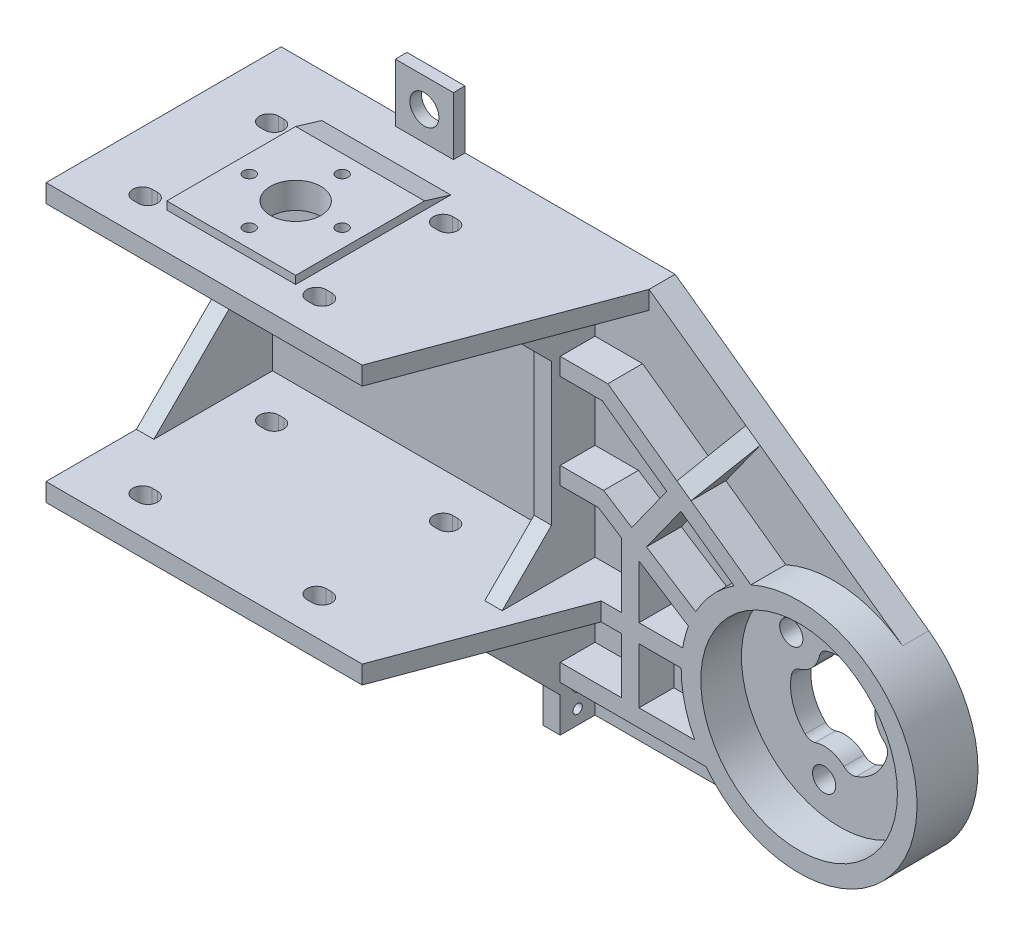
SolidWorks part; units mm, degrees
ref_plane "Alzado" through (0, 0, 0) normal (0, 0, 1) x (1, 0, 0)
ref_plane "Planta" through (0, 0, 0) normal (0, 1, 0) x (1, 0, 0)
ref_plane "Vista lateral" through (0, 0, 0) normal (1, 0, 0) x (0, 0, -1)
sketch "Croquis1" plane through (0, 0, 0) normal (0, 0, 1) x (1, 0, 0)
  line L1 (-98.9551, 43.6677) -> (22.1086, 43.6677)
  line L2 (-98.9551, 43.6677) -> (-98.9551, -24.473)
  line L3 (-98.9551, -24.473) -> (22.1086, -24.473)
  line L4 (22.1086, 43.6677) -> (22.1086, -24.473)
extrude "Saliente-Extruir1" add sketch "Croquis1" along normal blind 3 and the other way blind 1.5
sketch "Croquis2" plane through (0, 0, 3) normal (0, 0, 1) x (1, 0, 0)
  line L0 (-98.9551, 43.6677) -> (-98.9551, -24.473) construction
  line L1 (-98.9551, 43.6677) -> (-31.1073, 43.6677)
  line L2 (-98.9551, 43.6677) -> (-98.9551, 40.5377)
  line L3 (-98.9551, 40.5377) -> (-31.1073, 40.5377)
  line L4 (-31.1073, 43.6677) -> (-31.1073, 40.5377)
  line L5 (-98.9551, -4.0423) -> (-31.1073, -4.0423)
  line L6 (-98.9551, -4.0423) -> (-98.9551, -0.9123)
  line L7 (-98.9551, -0.9123) -> (-31.1073, -0.9123)
  line L8 (-31.1073, -4.0423) -> (-31.1073, -0.9123)
  dimension "D1" = 3.13
  dimension "D2" = 3.13
  dimension "D3" = 41.45
extrude "Saliente-Extruir2" add sketch "Croquis2" along normal blind 36
sketch "Croquis3" plane through (0, 43.6677, 0) normal (0, 1, 0) x (1, 0, 0)
  line L0 (-44.4942, -39) -> (-31.1073, -3)
  line L1 (-31.1073, -39) -> (-98.9551, -39) construction
  line L2 (-31.1073, -3) -> (-31.1073, -39)
  line L3 (-31.1073, -39) -> (-44.4942, -39)
extrude "Cortar-Extruir1" cut sketch "Croquis3" against normal up to surface (47.71 mm away) up to face at (-65.0312, -4.0423, 21)
sketch "Croquis4" plane through (-98.9551, 0, 0) normal (-1, 0, 0) x (0, 0, 1)
  line L0 (3, 40.5377) -> (23.4307, 40.5377)
  line L1 (39, 40.5377) -> (3, 40.5377) construction
  line L2 (23.4307, 40.5377) -> (3, 20.107)
  line L3 (3, 40.5377) -> (3, -0.9123) construction
  line L4 (3, 20.107) -> (3, 40.5377)
  line L5 (3, -4.0423) -> (23.4307, -4.0423)
  line L6 (39, -4.0423) -> (3, -4.0423) construction
  line L7 (23.4307, -4.0423) -> (3, -24.473)
  line L8 (3, -24.473) -> (3, -4.0423)
  line L9 (3, 19.5184) -> (3, -0.9123)
  line L10 (3, -0.9123) -> (23.4307, -0.9123)
  line L11 (39, -0.9123) -> (3, -0.9123) construction
  line L12 (23.4307, -0.9123) -> (3, 19.5184)
extrude "Saliente-Extruir3" add sketch "Croquis4" against normal blind 3
sketch "Croquis5" plane through (0, 0, 3) normal (0, 0, 1) x (1, 0, 0)
  line L11 (-31.1073, 43.6677) -> (21.0556, 6.2669)
  line L14 (40.0513, -24.473) -> (40.0513, 62.8259)
  line L15 (40.0513, 62.8259) -> (-31.1073, 62.8259)
  line L16 (-31.1073, 62.8259) -> (-31.1073, 43.6677)
  line L17 (-95.9551, -24.473) -> (22.1086, -24.473) construction
  line L18 (21.0556, -24.473) -> (21.0556, 6.2669)
  line L19 (21.0556, -24.473) -> (40.0513, -24.473)
  circle A4 centre (0.7449, -4.1623) radius 20.3107 construction
extrude "Cortar-Extruir2" cut sketch "Croquis5" against normal blind 4.5
ref_plane "Plano1" through (-44.4942, 0, 0) normal (-1, 0, 0) x (0, 0, 1)
hole_wizard "Taladro roscado M41" positions "Croquis7" profile "Croquis8" tap size "M4" standard "ISO"
sketch "Croquis7" plane through (0, 43.6677, 0) normal (0, 1, 0) x (1, 0, 0)
  point P0 (-88.3551, -10.7)
  point P3 (-58.3551, -10.6956)
  point P6 (-58.3551, -32.4956)
  point P9 (-88.3551, -32.5)
  dimension "D1" = 30
  dimension "D2" = 30
sketch "Croquis8" plane through (-88.3551, 43.6677, 10.7) normal (1, 0, 0) x (0, 0, 1)
  line L0 (0, 0) -> (0, 12.4914)
  line L1 (0, 12.4914) -> (1.65, 11.5)
  line L2 (1.65, 11.5) -> (1.65, 0)
  line L5 (1.65, 0) -> (0, 0)
  line L10 (0, 12.4914) -> (-1.65, 11.5) construction
  line L11 (0, -6.35) -> (0, 107.95) construction
  dimension "Diámetro de perforador para roscar" = 3.3
  dimension "Profundidad de perforador para roscar" = 11.5
  dimension "Ángulo de perforador" = 118
ref_plane "Plano2" through (0, 19.8127, 0) normal (0, 1, 0) x (1, 0, 0)
sketch "Croquis9" plane through (0, 43.6677, 0) normal (0, 1, 0) x (1, 0, 0)
  line L0 (-31.1073, 1.5) -> (-98.9551, 1.5) construction
  line L1 (-77.2938, 1.5) -> (-67.2938, 1.5)
  line L2 (-77.2938, 1.5) -> (-77.2938, -0.5)
  line L3 (-77.2938, -0.5) -> (-67.2938, -0.5)
  line L4 (-67.2938, 1.5) -> (-67.2938, -0.5)
  line L5 (-72.2938, -0.5) -> (-72.2938, -39) construction
  line L6 (-44.4942, -39) -> (-98.9551, -39) construction
  dimension "D1" = 2
  dimension "D2" = 10
extrude "Saliente-Extruir5" add sketch "Croquis9" along normal blind 10
sketch "Croquis10" plane through (0, 0, 0.5) normal (0, 0, 1) x (1, 0, 0)
  line L0 (-72.2938, 53.6677) -> (-72.2938, 48.6677) construction
  line L1 (-77.2938, 53.6677) -> (-67.2938, 53.6677) construction
  circle A0 centre (-72.2938, 48.6677) radius 2.5
  dimension "D2" = 5
  dimension "D1" = 5
extrude "Cortar-Extruir3" cut sketch "Croquis10" against normal blind 10
sketch "Croquis12" plane through (0, 43.6677, 0) normal (0, 1, 0) x (1, 0, 0)
  line L0 (-88.3551, -10.7) -> (-58.3551, -10.7) construction
  line L1 (-73.3551, -10.7) -> (-73.3551, -21.6) construction
  line L2 (-73.3551, -21.6) -> (-73.3551, -32.5) construction
  line L3 (-73.3551, -32.5) -> (-88.3551, -32.5) construction
  line L5 (-84.4551, -10.5) -> (-62.2551, -10.5)
  line L6 (-84.4551, -10.5) -> (-84.4551, -32.7)
  line L7 (-84.4551, -32.7) -> (-62.2551, -32.7)
  line L8 (-62.2551, -10.5) -> (-62.2551, -32.7)
  line L9 (-84.4551, -10.5) -> (-62.2551, -32.7) construction
  line L10 (-84.4551, -32.7) -> (-62.2551, -10.5) construction
  circle A0 centre (-73.3551, -21.6) radius 11.1 construction
  dimension "D1" = 22.2
extrude "Saliente-Extruir6" add sketch "Croquis12" along normal blind 1.37
sketch "Croquis13" plane through (0, 45.0377, 0) normal (0, 1, 0) x (1, 0, 0)
  line L0 (-84.4551, -10.5) -> (-84.4551, -32.7) construction
  line L1 (-62.2551, -32.7) -> (-62.2551, -10.5) construction
  line L2 (-62.2551, -10.5) -> (-84.4551, -10.5) construction
  circle A1 centre (-73.3551, -21.6) radius 8 construction
  circle A3 centre (-73.3551, -13.6) radius 1
  circle A4 centre (-81.3551, -21.6) radius 1
  circle A5 centre (-73.3551, -29.6) radius 1
  circle A6 centre (-65.3551, -21.6) radius 1
  circle A7 centre (-73.3551, -21.6) radius 11.1 construction
  circle A8 centre (-73.3551, -21.6) radius 4.35
  dimension "D1" = 16
  dimension "D2" = 2
  dimension "D3" = 8.7
extrude "Cortar-Extruir5" cut sketch "Croquis13" against normal up to surface (4.5 mm away) up to face at (-88.3551, 40.5377, 12.35)
sketch "Croquis14" plane through (0, 40.5377, 0) normal (0, -1, 0) x (1, 0, 0)
  circle A0 centre (-73.3551, 29.6) radius 2
  circle A1 centre (-81.3551, 21.6) radius 2
  circle A2 centre (-73.3551, 13.6) radius 2
  circle A3 centre (-65.3551, 21.6) radius 2
  dimension "D1" = 4
extrude "Cortar-Extruir6" cut sketch "Croquis14" against normal blind 2
sketch "Croquis15" plane through (-84.4551, 0, 0) normal (-1, 0, 0) x (0, 0, 1)
  line L0 (10.5, 45.0377) -> (10.5, 43.6677)
  line L1 (10.5, 43.6677) -> (5.991, 43.6677)
  line L2 (5.991, 43.6677) -> (10.5, 45.0377)
extrude "Saliente-Extruir7" add sketch "Croquis15" against normal up to surface (22.2 mm away) up to face at (-62.2551, 44.3527, 21.6)
ref_plane "Plano3" through (-43.3942, 0, 0) normal (-1, 0, 0) x (0, 0, 1)
sketch "Croquis16" plane through (-43.3942, 0, 0) normal (-1, 0, 0) x (0, 0, 1)
  line L0 (3, -0.9123) -> (23.4307, -0.9123) construction
  line L1 (3, -0.9123) -> (19, -0.9123)
  line L2 (3, -0.9123) -> (3, 40.5377)
  line L4 (10.5, 7.5877) -> (10.5, 32.0377)
  line L6 (3, 6.2669) -> (3, -24.473) construction
  line L7 (10.5, 7.5877) -> (19, -0.9123)
  line L9 (10.5, 32.0377) -> (19, 40.5377)
  line L11 (19, 40.5377) -> (3, 40.5377)
  line L12 (19, -0.9123) -> (19, 40.5377) construction
  line L13 (27.6, 40.5377) -> (31.6, 40.5377) construction
  dimension "D1" = 7.5
  dimension "D2" = 45
  dimension "D3" = 16
  dimension "D4" = 45
extrude "Saliente-Extruir8" add sketch "Croquis16" against normal blind 3
sketch "Croquis18" plane through (0, 0, 3) normal (0, 0, 1) x (1, 0, 0)
  line L0 (-95.9551, -24.473) -> (21.0556, -24.473) construction
  circle A0 centre (0.7449, -4.1623) radius 20.3107
  circle A1 centre (0.7449, -4.1623) radius 16.9357
extrude "Saliente-Extruir9" add sketch "Croquis18" along normal blind 6 contours A0 A1
sketch "Croquis19" plane through (0, 0, 3) normal (0, 0, 1) x (1, 0, 0)
  circle A0 centre (0.7449, -4.1623) radius 16.9357
extrude "Cortar-Extruir7" cut sketch "Croquis19" against normal blind 1
sketch "Croquis20" plane through (0, 0, 3) normal (0, 0, 1) x (1, 0, 0)
  circle A0 centre (0.7449, -4.1623) radius 8.4803
extrude "Cortar-Extruir8" cut sketch "Croquis20" against normal blind 8
sketch "Croquis21" plane through (0, 0, 2) normal (0, 0, 1) x (1, 0, 0)
  line L0 (0.7449, -4.1623) -> (0.7449, -26.4473) construction
  line L1 (0.7449, -4.1623) -> (-1.9409, -15.3443) construction
  line L2 (0.7449, -4.1623) -> (-7.5961, 3.7547) construction
  line L3 (0.7449, -4.1623) -> (11.7716, -0.8972) construction
  circle A3 centre (-1.9409, -15.3443) radius 2
  circle A4 centre (0.7449, -4.1623) radius 11.5 construction
  circle A5 centre (-7.5961, 3.7547) radius 2
  circle A6 centre (11.7716, -0.8972) radius 2
  dimension "D1" = 11.5
  dimension "D2" = 120
  dimension "D3" = 120
  dimension "D5" = 4
  dimension "D4" = 13.506
extrude "Cortar-Extruir9" cut sketch "Croquis21" against normal blind 8
sketch "Croquis22" plane through (-43.3942, 0, 0) normal (-1, 0, 0) x (0, 0, 1)
  line L0 (23.4307, -4.0423) -> (3, -24.473)
  line L1 (3, -24.473) -> (3, -4.0423)
  line L2 (3, -4.0423) -> (23.4307, -4.0423)
  line L3 (3, -24.473) -> (3, 16.1484) construction
  line L4 (39, -4.0423) -> (23.4307, -4.0423) construction
extrude "Saliente-Extruir10" add sketch "Croquis22" against normal blind 3
sketch "Croquis23" plane through (-43.3942, 0, 0) normal (-1, 0, 0) x (0, 0, 1)
  line L1 (9, -4.0423) -> (3, -4.0423)
  line L2 (9, -4.0423) -> (9, -0.9123)
  line L3 (9, -0.9123) -> (3, -0.9123)
  line L4 (3, -4.0423) -> (3, -0.9123)
  line L5 (3, -4.0423) -> (3, -24.473) construction
  line L6 (23.4307, -4.0423) -> (3, -4.0423) construction
  line L7 (3, -0.9123) -> (19, -0.9123) construction
  line L8 (9, -21.098) -> (9, 12.7734) construction
extrude "Saliente-Extruir11" add sketch "Croquis23" against normal blind 26
sketch "Croquis24" plane through (0, 0, 3) normal (0, 0, 1) x (1, 0, 0)
  line L0 (-40.3942, -13.6087) -> (-17.2354, -13.6087)
  line L1 (-40.3942, -24.473) -> (-40.3942, -4.0423) construction
  line L2 (-40.3942, -13.6087) -> (-40.3942, -16.6087)
  line L3 (-40.3942, -16.6087) -> (-15.3054, -16.6087)
  line L4 (-40.3942, 32.0377) -> (-32.2036, 32.0377)
  line L5 (-32.2036, 32.0377) -> (-20.2999, 23.5028)
  line L6 (-40.3942, 29.0377) -> (-33.1679, 29.0377)
  line L7 (-40.3942, 7.5877) -> (-40.3942, 32.0377) construction
  line L8 (-33.1679, 29.0377) -> (-22.048, 21.0648)
  line L9 (-40.3942, 32.0377) -> (-40.3942, 29.0377)
  line L10 (-31.1073, 43.6677) -> (12.5799, 12.344) construction
  line L11 (-40.3942, 15.7676) -> (-32.9238, 15.7676)
  line L12 (-32.9238, 15.7676) -> (-28.0751, 12.6589)
  line L13 (-40.3942, 12.7676) -> (-33.8029, 12.7676)
  line L14 (-33.8029, 12.7676) -> (-18.3202, 2.841)
  line L15 (-40.3942, 15.7676) -> (-40.3942, 12.7676)
  line L16 (-29.8255, -13.6087) -> (-29.8255, 10.2175)
  line L17 (-26.8255, -13.6087) -> (-26.8255, 8.2941)
  line L18 (-25.5461, 11.0375) -> (-19.61, 19.3167)
  line L19 (-11.9822, 29.9551) -> (-14.4203, 31.7032)
  line L20 (-14.4203, 31.7032) -> (-20.2999, 23.5028)
  line L21 (-19.61, 19.3167) -> (-10.4759, 12.7676)
  line L22 (-17.8619, 21.7547) -> (-7.564, 14.3712)
  line L23 (-22.048, 21.0648) -> (-28.0751, 12.6589)
  line L24 (-17.8619, 21.7547) -> (-11.9822, 29.9551)
  line L25 (-25.5461, 11.0375) -> (-17.0657, 5.6003)
  arc A0 (-19.5655, -4.0423) -> (-19.3041, -0.9123) centre (0.7449, -4.1623) ccw construction
  arc A2 (-17.2354, -13.6087) -> (-15.3054, -16.6087) centre (0.7449, -4.1623) ccw
  arc A3 (-7.564, 14.3712) -> (-10.4759, 12.7676) centre (0.7449, -4.1623) ccw
  arc A4 (-19.5655, -4.0423) -> (-15.3054, -16.6087) centre (0.7449, -4.1623) ccw
  arc A5 (-17.0657, 5.6003) -> (-18.3202, 2.841) centre (0.7449, -4.1623) ccw
  arc A6 (-7.564, 14.3712) -> (-10.4759, 12.7676) centre (0.7449, -4.1623) ccw
  line M22 (-40.3942, -0.9123) -> (-19.3041, -0.9123)
  arc M23 (-19.3041, -0.9123) -> (12.5799, 12.344) centre (0.7449, -4.1623) cw
  line M24 (12.5799, 12.344) -> (-31.1073, 43.6677)
  line M27 (-40.3942, 40.5377) -> (-40.3942, -0.9123)
  dimension "D1" = 3
  dimension "D2" = 3
  dimension "D3" = 3
  dimension "D4" = 3
  dimension "D5" = 3
  dimension "D6" = 3
  dimension "D7" = 3
extrude "Saliente-Extruir12" add sketch "Croquis24" along normal blind 6 contours L17 L14 L16 M22 | L25 L18 L21 L22 L24 L20 L5 L4 L6 L8 L23 L12 L11 L13 L14 M23 M24 M27 | L0 L17 L16 M22 | A2 L0 L2 L3
sketch "Croquis25" plane through (-22.0991, 15.8451, 0) normal (0.8127, -0.5827, 0) x (0, 0, -1)
  line L0 (-9, 7.2718) -> (-3, 17.3621)
  line L1 (-3, 17.3621) -> (-9, 17.3621)
  line L2 (-9, 17.3621) -> (-9, 7.2718)
extrude "Cortar-Extruir10" cut sketch "Croquis25" against normal up to surface (3 mm away) up to face at (-17.3601, 27.603, 6)
sketch "Croquis26" plane through (0, 0, 3) normal (0, 0, 1) x (1, 0, 0)
  line L0 (0.7449, -24.473) -> (0.7449, -33.4143)
  line L1 (0.7449, -33.4143) -> (41.987, -33.4143)
  line L2 (41.987, -33.4143) -> (41.987, 16.9721)
  line L3 (41.987, 16.9721) -> (26.4135, 31.6378)
  line L4 (26.4135, 31.6378) -> (12.5799, 12.344)
  line L5 (12.5799, 12.344) -> (21.0556, 6.2669) construction
  arc A0 (0.7449, -24.473) -> (21.0556, -4.1623) centre (0.7449, -4.1623) ccw construction
  arc A1 (21.0556, -4.1623) -> (12.5799, 12.344) centre (0.7449, -4.1623) ccw construction
  arc A2 (0.7449, -24.473) -> (21.0556, -4.1623) centre (0.7449, -4.1623) ccw
  arc A3 (21.0556, -4.1623) -> (12.5799, 12.344) centre (0.7449, -4.1623) ccw
extrude "Cortar-Extruir11" cut sketch "Croquis26" against normal blind 26
sketch "Croquis27" plane through (0, 0, 3) normal (0, 0, 1) x (1, 0, 0)
  line L0 (-72.2938, 48.6677) -> (-72.2938, -15.0076) construction
  line L1 (-72.2938, -15.0076) -> (-84.7938, -15.0076) construction
  line L2 (-72.2938, -15.0076) -> (-59.7938, -15.0076) construction
  circle A0 centre (-84.7938, -15.0076) radius 2.5
  circle A1 centre (-59.7938, -15.0076) radius 2.5
  dimension "D1" = 5
  dimension "D2" = 25
extrude "Cortar-Extruir12" cut sketch "Croquis27" against normal blind 26
sketch "Croquis28" plane through (0, 43.6677, 0) normal (0, 1, 0) x (1, 0, 0)
  line L0 (-88.8452, -30.85) -> (-87.9176, -30.85)
  line L1 (-88.8452, -9.05) -> (-87.954, -9.05)
  line L2 (-88.8452, -9.05) -> (-88.8452, -12.35) construction
  line L3 (-88.8452, -12.35) -> (-87.954, -12.35)
  line L4 (-87.954, -9.05) -> (-87.954, -12.35) construction
  line L5 (-88.8452, -30.85) -> (-88.8452, -34.15) construction
  line L6 (-88.8452, -34.15) -> (-87.9176, -34.15)
  line L7 (-87.9176, -30.85) -> (-87.9176, -34.15) construction
  line L8 (-58.8776, -30.8456) -> (-57.895, -30.8456)
  line L9 (-58.8776, -30.8456) -> (-58.8776, -34.1456) construction
  line L10 (-58.8776, -34.1456) -> (-57.895, -34.1456)
  line L11 (-57.895, -30.8456) -> (-57.895, -34.1456) construction
  line L12 (-58.8776, -9.0456) -> (-57.9865, -9.0456)
  line L13 (-58.8776, -9.0456) -> (-58.8776, -12.3456) construction
  line L14 (-58.8776, -12.3456) -> (-57.9865, -12.3456)
  line L15 (-57.9865, -9.0456) -> (-57.9865, -12.3456) construction
  line L16 (-88.8452, -32.5) -> (-57.895, -32.4956) construction
  line L17 (-88.8452, -10.7) -> (-88.8452, -32.5) construction
  line L18 (-88.8452, -10.7) -> (-58.8776, -10.6956) construction
  line L19 (-58.8776, -10.6956) -> (-58.8776, -32.4956) construction
  arc A0 (-88.8452, -30.85) -> (-88.8452, -34.15) centre (-88.8452, -32.5) ccw
  arc A1 (-88.8452, -9.05) -> (-88.8452, -12.35) centre (-88.8452, -10.7) ccw
  arc A2 (-87.954, -9.05) -> (-87.954, -12.35) centre (-87.954, -10.7) cw
  arc A3 (-87.9176, -30.85) -> (-87.9176, -34.15) centre (-87.9176, -32.5) cw
  arc A4 (-58.8776, -30.8456) -> (-58.8776, -34.1456) centre (-58.8776, -32.4956) ccw
  arc A5 (-57.895, -30.8456) -> (-57.895, -34.1456) centre (-57.895, -32.4956) cw
  arc A6 (-58.8776, -9.0456) -> (-58.8776, -12.3456) centre (-58.8776, -10.6956) ccw
  arc A7 (-57.9865, -9.0456) -> (-57.9865, -12.3456) centre (-57.9865, -10.6956) cw
  circle A8 centre (-88.3551, -32.5) radius 1.65 construction
extrude "Cortar-Extruir13" cut sketch "Croquis28" against normal blind 79
sketch "Croquis29" plane through (-40.3942, 0, 0) normal (1, 0, 0) x (0, 0, -1)
  line L1 (-3, -16.6087) -> (-9, -16.6087)
  line L2 (-3, -16.6087) -> (-3, -24.473)
  line L3 (-3, -24.473) -> (-9, -24.473)
  line L4 (-9, -16.6087) -> (-9, -24.473)
extrude "Saliente-Extruir13" add sketch "Croquis29" against normal blind 3
sketch "Croquis30" plane through (-43.3942, 0, 0) normal (-1, 0, 0) x (0, 0, 1)
  line L0 (6, -24.473) -> (6, -18.7149) construction
  line L1 (9, -24.473) -> (3, -24.473) construction
  circle A0 centre (6, -18.7149) radius 1
  circle A1 centre (6, -22.0334) radius 1
  dimension "D1" = 2
  dimension "D2" = 2
hole_wizard "Taladro roscado M21" positions "Croquis31" profile "Croquis32" tap size "M2" standard "ISO"
sketch "Croquis31" plane through (-43.3942, 0, 0) normal (-1, 0, 0) x (0, 0, 1)
  point P0 (6, -18.7149)
  point P3 (6, -22.0334)
sketch "Croquis32" plane through (-43.3942, -18.7149, 6) normal (0, 1, 0) x (0, 0, 1)
  line L0 (0, 0) -> (0, 6.4807)
  line L1 (0, 6.4807) -> (0.8, 6)
  line L2 (0.8, 6) -> (0.8, 0)
  line L5 (0.8, 0) -> (0, 0)
  line L10 (0, 6.4807) -> (-0.8, 6) construction
  line L11 (0, -6.35) -> (0, 107.95) construction
  dimension "Diámetro de perforador para roscar" = 1.6
  dimension "Profundidad de perforador para roscar" = 6
  dimension "Ángulo de perforador" = 118
sketch "Croquis33" plane through (0, 0, -1.5) normal (0, 0, -1) x (-1, 0, 0)
  arc A0 (-8.4357, -4.5891) -> (-6.9237, 0.2236) centre (-11.7716, -0.8972) ccw
  circle A3 centre (-0.7449, -4.1623) radius 8.4803 construction
  arc A4 (-6.2366, 2.2997) -> (-8.949, -6.3091) centre (-0.7449, -4.1623) ccw
  arc A5 (-6.9237, 0.2236) -> (-6.2366, 2.2997) centre (-4.8747, 0.6973) cw
  arc A6 (-8.4357, -4.5891) -> (-8.949, -6.3091) centre (-7.2769, -5.8715) ccw
extrude "Saliente-Extruir14" add sketch "Croquis33" against normal up to surface (3.5 mm away) up to face at (-5.5961, 3.7547, 2)
pattern_circular "MatrizC1" count 3 over 360 about axis through (0.7449, -4.1623, 0) along (0, 0, 1) of "Saliente-Extruir14"
